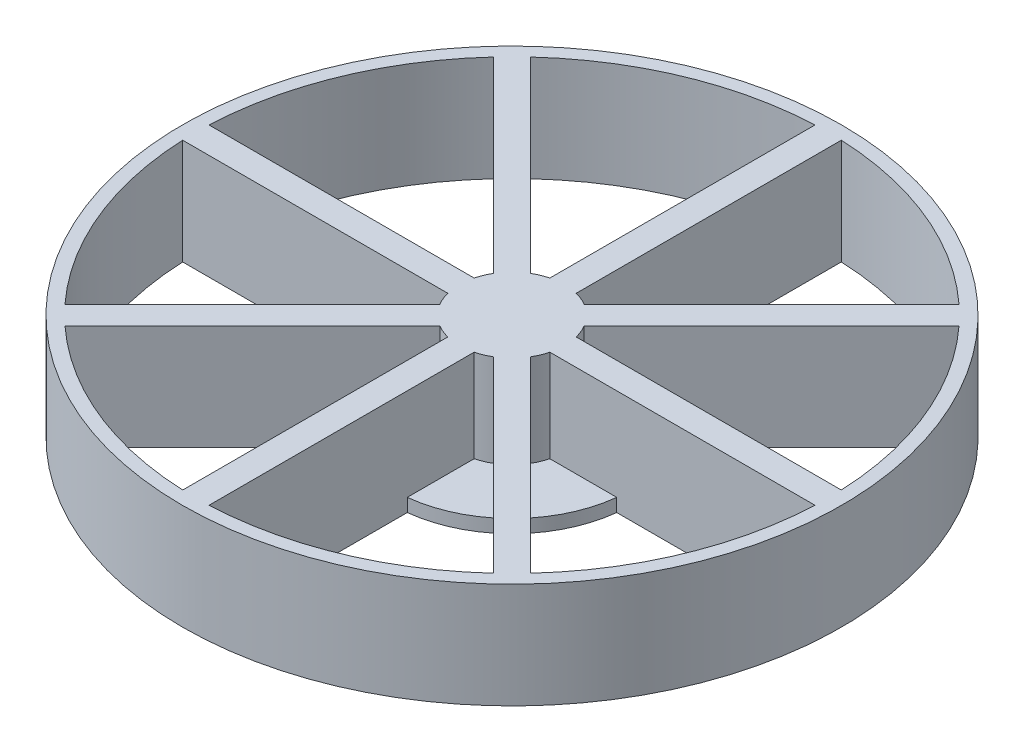
SolidWorks part; units mm, degrees
ref_plane "Front Plane" through (0, 0, 0) normal (0, 0, 1) x (1, 0, 0)
ref_plane "Top Plane" through (0, 0, 0) normal (0, 1, 0) x (1, 0, 0)
ref_plane "Right Plane" through (0, 0, 0) normal (1, 0, 0) x (0, 0, -1)
sketch "Sketch1" plane through (0, 0, 0) normal (0, 1, 0) x (1, 0, 0)
  line L4 (9.4387, -4.9486) -> (4.9486, -9.4387)
  line L5 (10.1734, 3.175) -> (78.401, 3.175)
  line L6 (10.1734, 3.175) -> (10.1734, -3.175)
  line L7 (10.1734, -3.175) -> (78.401, -3.175)
  line L8 (78.401, 3.175) -> (78.401, -3.175)
  line L9 (9.4387, -4.9486) -> (57.683, -53.1928)
  line L10 (57.683, -53.1928) -> (53.1928, -57.683)
  line L11 (4.9486, -9.4387) -> (53.1928, -57.683)
  line L12 (3.175, -10.1734) -> (-3.175, -10.1734)
  line L13 (3.175, -10.1734) -> (3.175, -78.401)
  line L14 (3.175, -78.401) -> (-3.175, -78.401)
  line L15 (-3.175, -10.1734) -> (-3.175, -78.401)
  line L16 (-4.9486, -9.4387) -> (-9.4387, -4.9486)
  line L17 (-4.9486, -9.4387) -> (-53.1928, -57.683)
  line L18 (-53.1928, -57.683) -> (-57.683, -53.1928)
  line L19 (-9.4387, -4.9486) -> (-57.683, -53.1928)
  line L20 (-10.1734, -3.175) -> (-10.1734, 3.175)
  line L21 (-10.1734, -3.175) -> (-78.401, -3.175)
  line L22 (-78.401, -3.175) -> (-78.401, 3.175)
  line L23 (-10.1734, 3.175) -> (-78.401, 3.175)
  line L24 (-9.4387, 4.9486) -> (-4.9486, 9.4387)
  line L25 (-9.4387, 4.9486) -> (-57.683, 53.1928)
  line L26 (-57.683, 53.1928) -> (-53.1928, 57.683)
  line L27 (-4.9486, 9.4387) -> (-53.1928, 57.683)
  line L28 (-3.175, 10.1734) -> (3.175, 10.1734)
  line L29 (-3.175, 10.1734) -> (-3.175, 78.401)
  line L30 (-3.175, 78.401) -> (3.175, 78.401)
  line L31 (3.175, 10.1734) -> (3.175, 78.401)
  line L32 (4.9486, 9.4387) -> (9.4387, 4.9486)
  line L33 (4.9486, 9.4387) -> (53.1928, 57.683)
  line L34 (53.1928, 57.683) -> (57.683, 53.1928)
  line L35 (9.4387, 4.9486) -> (57.683, 53.1928)
  circle A0 centre (0, 0) radius 12.7
  circle A1 centre (0, 0) radius 79.375
  circle A2 centre (0, 0) radius 76.2
  circle A3 centre (0, 0) radius 28.575
  point P40 (0, 0)
  dimension "D1" = 25.4
  dimension "D2" = 158.75
  dimension "D3" = 152.4
  dimension "D7" = 57.15
  dimension "D4" = 6.35
  dimension "D5" = 3.175
  dimension "D6" = 8
extrude "Boss-Extrude1" add sketch "Sketch1" along normal blind 25.4 contours L13 A0 L11 L4 L9 L7 L6 L5 L35 L32 L33 L31 L28 L29 L27 L24 L25 L23 L20 L21 L19 L16 L17 L15 L12 | A3 L27 A2 L25 | L27 A3 L25 A0 | A3 L31 A2 L29 | A3 L35 A2 L33 | A3 L7 A2 L5 | L35 A3 L33 A0 | L7 A3 L5 A0 | L11 A3 L9 A0 | A3 L11 A2 L9 | A3 L15 A2 L13 | L15 A3 L13 A0 | L19 A3 L17 A0 | L23 A3 L21 A0 | A3 L23 A2 L21 | A2 L23 L22 L21 | A1 A2 L13 L14 L15 L17 L18 L19 L21 L22 L23 L25 L26 L27 L29 L30 L31 L33 L34 L35 L5 L8 L7 L9 L10 L11
sketch "Sketch2" plane through (0, 0, 0) normal (0, -1, 0) x (1, 0, 0)
  circle A0 centre (0, 0) radius 28.575
  dimension "D1" = 57.15
extrude "Boss-Extrude2" add sketch "Sketch2" against normal blind 3.175
sketch "Sketch3" plane through (0, 0, 0) normal (0, -1, 0) x (1, 0, 0)
  circle A0 centre (0, 0) radius 9.525
  dimension "D1" = 19.05
extrude "Cut-Extrude1" cut sketch "Sketch3" against normal blind 19.05
